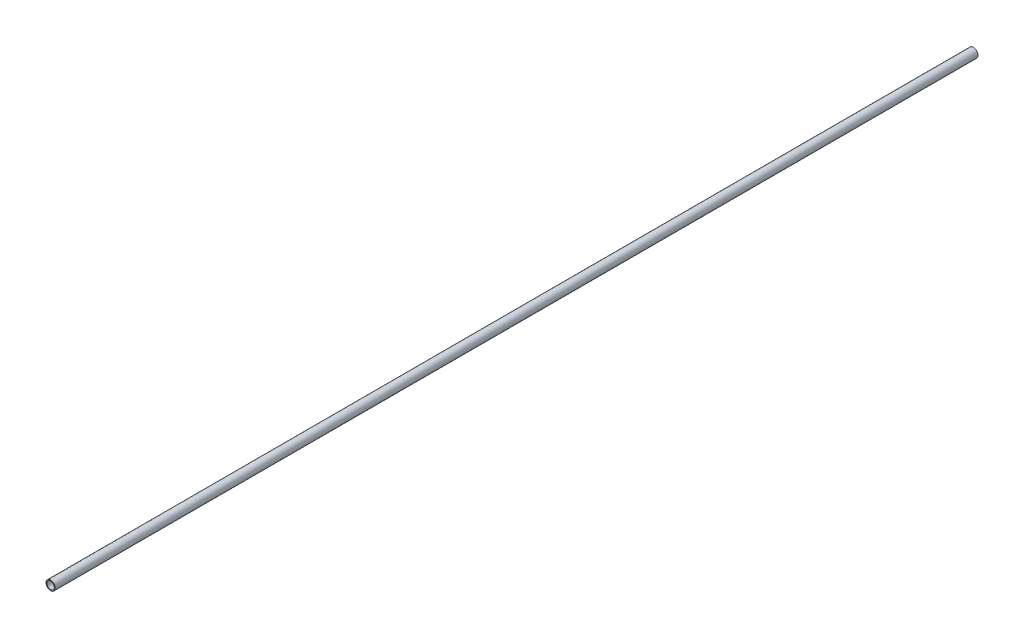
SolidWorks part; units mm, degrees
material "Плетеная трубка"
ref_plane "Front Plane" through (0, 0, 0) normal (0, 0, 1) x (1, 0, 0)
ref_plane "Top Plane" through (0, 0, 0) normal (0, 1, 0) x (1, 0, 0)
ref_plane "Right Plane" through (0, 0, 0) normal (1, 0, 0) x (0, 0, -1)
sketch "Sketch1" plane through (0, 0, 0) normal (0, 0, 1) x (1, 0, 0)
  circle A0 centre (0, 0) radius 5
  dimension "D1" = 10
extrude "Boss-Extrude1" add sketch "Sketch1" along normal mid plane 1000
shell "Shell1" thickness 1
